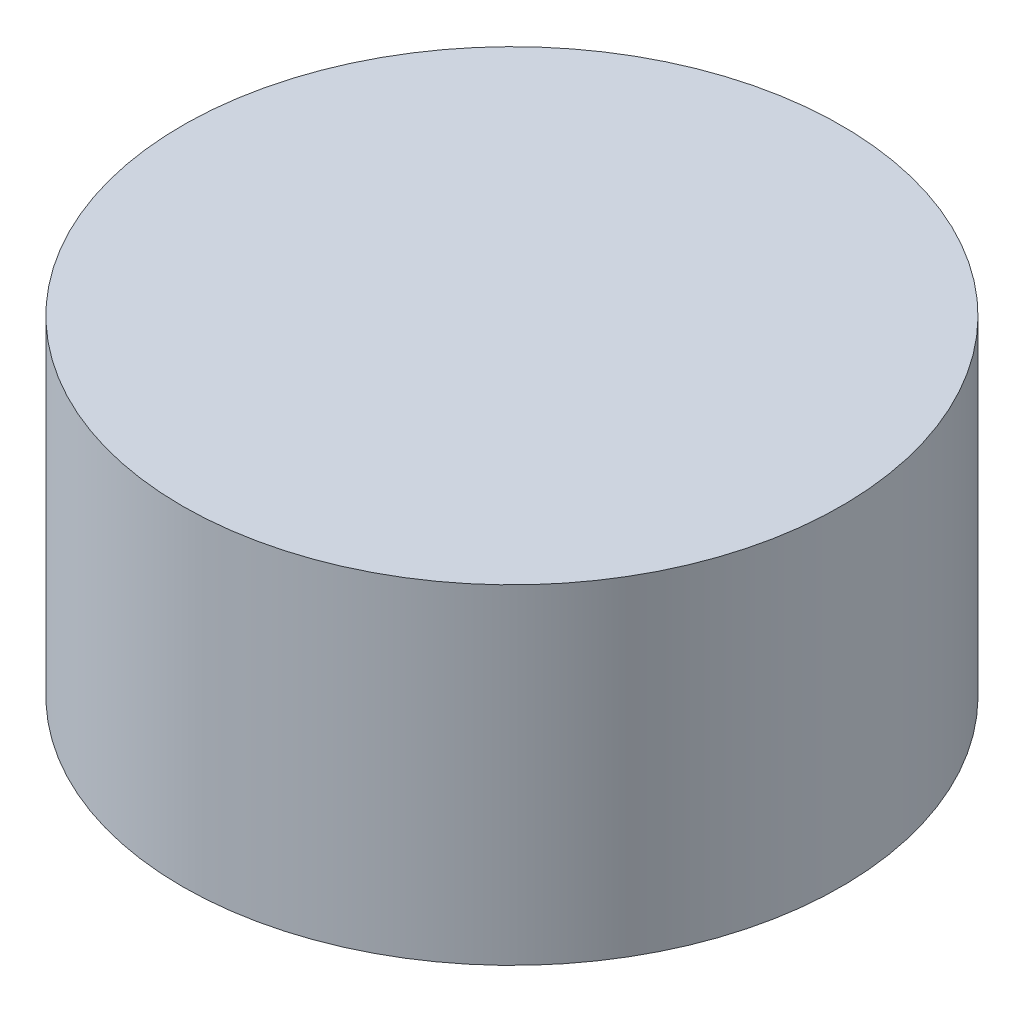
SolidWorks part; units mm, degrees
ref_plane "Front Plane" through (0, 0, 0) normal (0, 0, 1) x (1, 0, 0)
ref_plane "Top Plane" through (0, 0, 0) normal (0, 1, 0) x (1, 0, 0)
ref_plane "Right Plane" through (0, 0, 0) normal (1, 0, 0) x (0, 0, -1)
sketch "Sketch1" plane through (0, 0, 0) normal (0, 1, 0) x (1, 0, 0)
  circle A0 centre (0, 0) radius 25.4
extrude "Boss-Extrude1" add sketch "Sketch1" along normal blind 25.4
shell "Shell1" thickness 2.54
